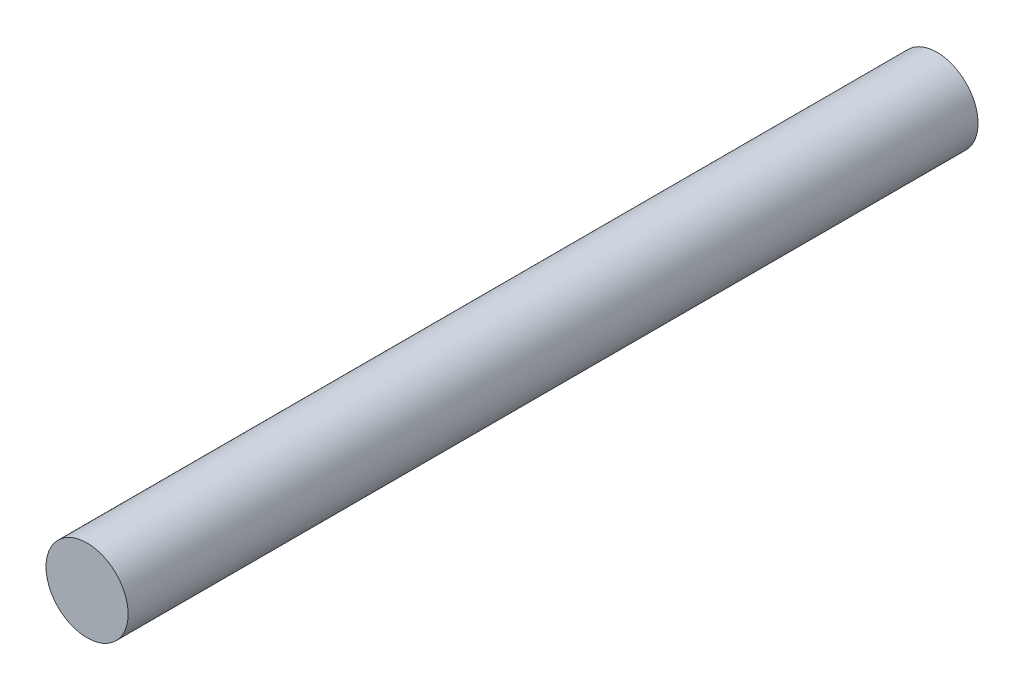
SolidWorks part; units mm, degrees
ref_plane "Front Plane" through (0, 0, 0) normal (0, 0, 1) x (1, 0, 0)
ref_plane "Top Plane" through (0, 0, 0) normal (0, 1, 0) x (1, 0, 0)
ref_plane "Right Plane" through (0, 0, 0) normal (1, 0, 0) x (0, 0, -1)
sketch "Sketch1" plane through (0, 0, 0) normal (0, 0, 1) x (1, 0, 0)
  circle A0 centre (0, 0) radius 4.7625
  dimension "D1" = 9.525
extrude "Boss-Extrude1" add sketch "Sketch1" along normal blind 98.552
equation "\"Wheel Thickness\"= 1in"
equation "\"Wheel Diameter\"= 3in"
equation "\"Motor Rear Diameter\" = 36.2mm"
equation "\"Motor Front Diameter\" = 12mm"
equation "\"Material Thickness\" = .25in"
equation "\"Wheel Cutout Diameter\"= 2cm"
equation "\"Motor Mount Tab Thickness\" = 100mm"
equation "\"Motor Mount Tab Height\" = 40mm"
equation "\"Motor Shaft Diameter\" = 3mm"
equation "\"Wheel Radius Clearance\" = 5mm"
equation "\"Wheel Cutout Width\" = 1.5in"
equation "\"Base Diameter\" = 10in"
equation "\"Wheel Mount Distance\" = 5mm"
equation "\"Motor Mount Distance\" = 50mm"
equation "\"Motor Cutout Length\" = 6in"
equation "\"Motor Cutout Height\" = 2in "
equation "\"Rod Diameter\" = 3/8in"
equation "\"Rod Length\" = 1.5in"
equation "\"Barrel Front Length\" = 1.8in"
equation "\"Barrerl Rear Length\" = 5in "
equation "\"Barrel Fillet Radius\" = 1in "
equation "\"Barrel Angle\" = 20deg"
equation "\"Barrel Diameter\" = 50mm"
equation "\"Barrel Shell Width\" = 2mm"
equation "\"Second Level Diameter\" = 10in"
equation "\"Ball Diameter\" = 40mm"
equation "\"Third Level Length\" = 9in"
equation "\"Third Level Height\" = 9in"
equation "\"Barrel Tab Clearance\" = 5mm"
equation "\"Barrel Tab Distance Away\" = 2mm"
equation "\"Hole Distance Apart\" = 2.8in"
equation "\"Barrel Tab Distance\"= 1.5in "
equation "\"Third Level Rod Distance\" = .5in"
equation " \"Second Rod Diameter\" = 3/8in"
equation "\"Second Rod Length\" = 3.88in"
equation "\"D1@Sketch1\"=\"Second Rod Diameter\""
equation "\"D1@Boss-Extrude1\"=\"Second Rod Length\""
